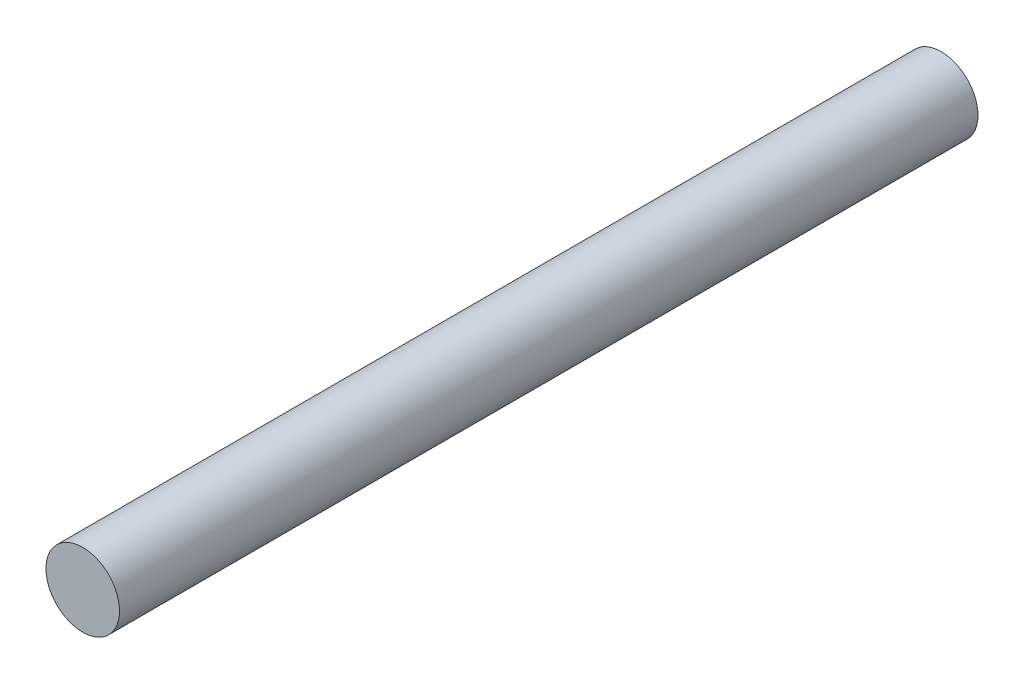
SolidWorks part; units mm, degrees
ref_plane "Front Plane" through (0, 0, 0) normal (0, 0, 1) x (1, 0, 0)
ref_plane "Top Plane" through (0, 0, 0) normal (0, 1, 0) x (1, 0, 0)
ref_plane "Right Plane" through (0, 0, 0) normal (1, 0, 0) x (0, 0, -1)
sketch "Sketch1" plane through (0, 0, 0) normal (0, 0, 1) x (1, 0, 0)
  circle A0 centre (0, 0) radius 1.5
  dimension "D1" = 3
extrude "Boss-Extrude1" add sketch "Sketch1" along normal blind 35
